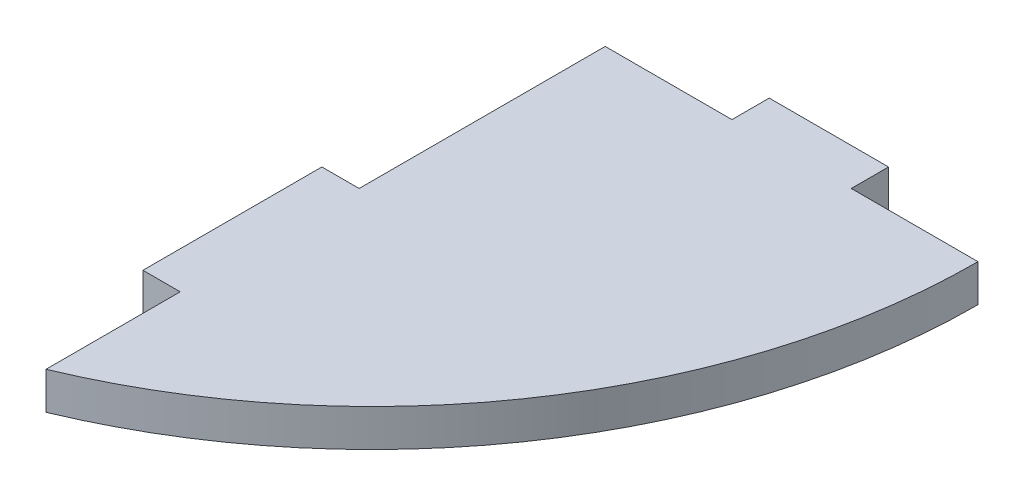
SolidWorks part; units mm, degrees
ref_plane "Front Plane" through (0, 0, 0) normal (0, 0, 1) x (1, 0, 0)
ref_plane "Top Plane" through (0, 0, 0) normal (0, 1, 0) x (1, 0, 0)
ref_plane "Right Plane" through (0, 0, 0) normal (1, 0, 0) x (0, 0, -1)
sketch "Sketch1" plane through (0, 0, 0) normal (0, 1, 0) x (1, 0, 0)
  line L0 (0, 26.67) -> (3.175, 26.67)
  line L1 (34.925, 47.625) -> (34.925, 17.4892) construction
  line L2 (0, 11.43) -> (0, 26.67)
  line L3 (13.97, 50.8) -> (24.13, 50.8)
  line L5 (3.175, 26.67) -> (3.175, 47.625)
  line L6 (0, 11.43) -> (3.175, 11.43)
  line L7 (3.175, 11.43) -> (3.175, 0)
  line L8 (13.97, 47.625) -> (3.175, 47.625)
  line L9 (24.13, 47.625) -> (34.925, 47.625)
  line L10 (13.97, 50.8) -> (13.97, 47.625)
  line L12 (24.13, 50.8) -> (24.13, 47.625)
  arc A1 (34.925, 47.625) -> (3.175, 0) centre (-16.6688, 47.625) cw
  dimension "D3" = 3.175
  dimension "D4" = 24.13
  dimension "D5" = 15.24
  dimension "D6" = 10.16
  dimension "D7" = 3.175
  dimension "D8" = 13.97
extrude "Boss-Extrude1" add sketch "Sketch1" along normal blind 3.175
